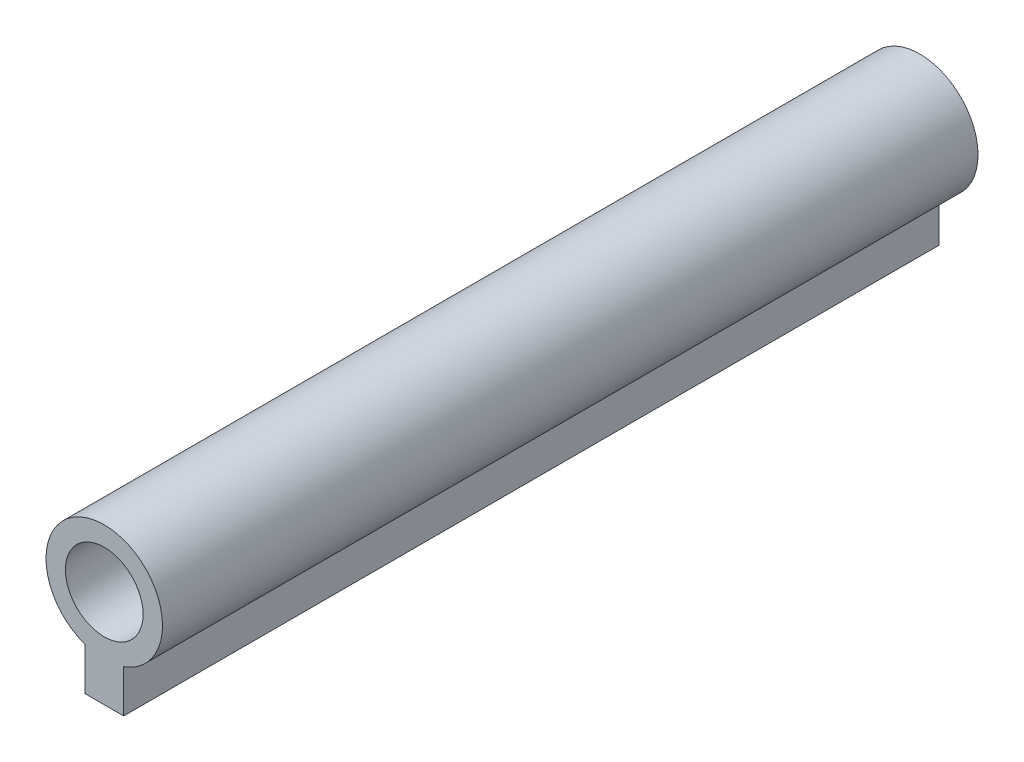
SolidWorks part; units mm, degrees
material "AISI 1020"
ref_plane "Front Plane" through (0, 0, 0) normal (0, 0, 1) x (1, 0, 0)
ref_plane "Top Plane" through (0, 0, 0) normal (0, 1, 0) x (1, 0, 0)
ref_plane "Right Plane" through (0, 0, 0) normal (1, 0, 0) x (0, 0, -1)
sketch "Sketch1" plane through (0, 0, 0) normal (0, 0, 1) x (1, 0, 0)
  circle A0 centre (0, 0) radius 5
  dimension "D1" = 10
extrude "Boss-Extrude1" add sketch "Sketch1" along normal blind 21
sketch "Sketch2" plane through (0, 0, 0) normal (0, 0, -1) x (-1, 0, 0)
  line L6 (-0.5, -1.4142) -> (-0.5, -2.5142)
  line L7 (-0.5, -2.5142) -> (0.5, -2.5142)
  line L8 (0.5, -1.4142) -> (0.5, -2.5142)
  arc A1 (0.5, -1.4142) -> (-0.5, -1.4142) centre (0, 0) ccw
  point P3 (0, -1.5)
  dimension "D1" = 3
  dimension "D2" = 1.1
  dimension "D3" = 1
extrude "Cut-Extrude1" cut sketch "Sketch2" against normal through all both and the other way through all flip side to cut
sketch "Sketch3" plane through (0, 0, 21) normal (0, 0, 1) x (1, 0, 0)
  circle A1 centre (0, 0) radius 11
  dimension "D1" = 22
extrude "Boss-Extrude2" [suppressed] add sketch "Sketch3" along normal blind 6
sketch "Sketch4" [suppressed] plane through (0, 0, 16) normal (0, 0, 1) x (1, 0, 0)
  circle A0 centre (0, 0) radius 8 construction
  circle A1 centre (0, 8) radius 1
  circle A2 centre (6.9282, 4) radius 1
  circle A3 centre (6.9282, -4) radius 1
  circle A4 centre (0, -8) radius 1
  circle A5 centre (-6.9282, -4) radius 1
  circle A6 centre (-6.9282, 4) radius 1
  point P18 (0, 0)
  dimension "D1" = 16
  dimension "D2" = 2
  dimension "D3" = 6
extrude "Cut-Extrude2" [suppressed] cut sketch "Sketch4" against normal through all
sketch "Sketch5" [suppressed] plane through (0, 0, 16) normal (0, 0, 1) x (1, 0, 0)
  circle A0 centre (0, 0) radius 4
  dimension "D1" = 8
extrude "Cut-Extrude3" [suppressed] cut sketch "Sketch5" against normal blind 5.5
sketch "Sketch6" plane through (0, 0, 21) normal (0, 0, 1) x (1, 0, 0)
  circle A0 centre (0, 0) radius 1
  dimension "D1" = 2
extrude "Cut-Extrude4" cut sketch "Sketch6" against normal blind 6
